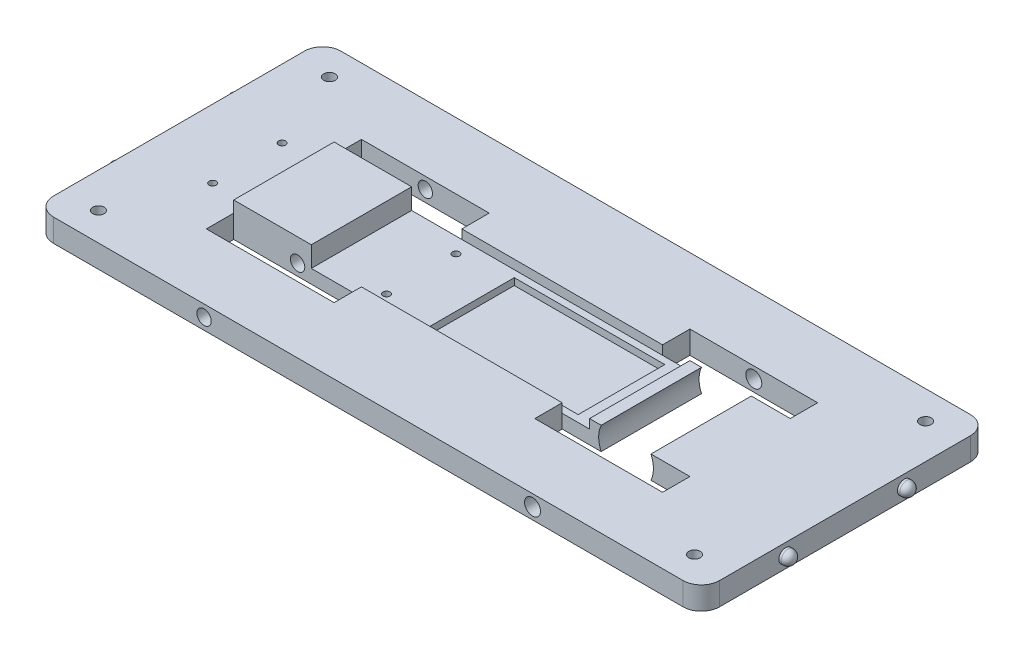
SolidWorks part; units mm, degrees
ref_plane "Front Plane" through (0, 0, 0) normal (0, 0, 1) x (1, 0, 0)
ref_plane "Top Plane" through (0, 0, 0) normal (0, 1, 0) x (1, 0, 0)
ref_plane "Right Plane" through (0, 0, 0) normal (1, 0, 0) x (0, 0, -1)
sketch "Sketch1" plane through (0, 0, 0) normal (0, 1, 0) x (1, 0, 0)
  line L1 (-69, 31.5) -> (69, 31.5)
  line L2 (-69, 31.5) -> (-69, -31.5)
  line L3 (-69, -31.5) -> (69, -31.5)
  line L4 (69, 31.5) -> (69, -31.5)
  line L5 (-69, 31.5) -> (69, -31.5) construction
  line L6 (-69, -31.5) -> (69, 31.5) construction
  point P0 (0, 0)
  dimension "D1" = 138
  dimension "D2" = 63
extrude "Boss-Extrude1" add sketch "Sketch1" along normal mid plane 5
sketch "Sketch3" plane through (0, 2.5, 0) normal (0, 1, 0) x (1, 0, 0)
  line L1 (-50, -11) -> (-22, -11)
  line L2 (-50, -11) -> (-50, -17)
  line L3 (-50, -17) -> (-22, -17)
  line L4 (-22, -11) -> (-22, -17)
  line L6 (0, -2.75) -> (0, 2.75) construction
  line L7 (50, -17) -> (22, -17)
  line L8 (22, -11) -> (22, -17)
  line L9 (50, -11) -> (22, -11)
  line L10 (50, -11) -> (50, -17)
  line L11 (-2.75, 0) -> (2.75, 0) construction
  line L12 (50, 11) -> (50, 17)
  line L13 (50, 11) -> (22, 11)
  line L14 (22, 11) -> (22, 17)
  line L15 (50, 17) -> (22, 17)
  line L16 (-50, 17) -> (-22, 17)
  line L17 (-22, 11) -> (-22, 17)
  line L18 (-50, 11) -> (-22, 11)
  line L19 (-50, 11) -> (-50, 17)
  dimension "D1" = 22
  dimension "D2" = 6
  dimension "D3" = 28
extrude "Cut-Extrude2" cut sketch "Sketch3" against normal blind 10
sketch "Sketch4" plane through (0, 2.5, 0) normal (0, 1, 0) x (1, 0, 0)
  line L0 (-22, -11) -> (-50, -11) construction
  line L1 (-33, -11) -> (28, -11)
  line L2 (-33, -11) -> (-33, 11)
  line L3 (-33, 11) -> (28, 11)
  line L4 (28, -11) -> (28, 11)
  line L5 (22, 11) -> (50, 11) construction
  line L6 (-50, -11) -> (-50, -17) construction
  line L7 (50, -17) -> (50, -11) construction
  dimension "D1" = 17
  dimension "D2" = 22
extrude "Cut-Extrude3" cut sketch "Sketch4" against normal blind 2
sketch "Sketch5" plane through (0, 0, -11) normal (0, 0, -1) x (-1, 0, 0)
  line L2 (50, -2.5) -> (50, 2.5) construction
  line L4 (0, 2.5) -> (0, -2.563)
  line L5 (-69, 2.5) -> (69, 2.5) construction
  line L6 (0, 2.75) -> (0, -2.75) construction
  line L7 (22, 2.5) -> (50, 2.5) construction
  circle A0 centre (36, 0) radius 1.575
  circle A3 centre (-36, 0) radius 1.75
  dimension "D1" = 3.15
  dimension "D4" = 3.5
  dimension "D2" = 2.5
  dimension "D3" = 14
sketch "Sketch6" plane through (0, 0.5, 0) normal (0, 1, 0) x (1, 0, 0)
  line L0 (-2.75, 0) -> (2.75, 0) construction
  line L1 (-9, -9.5) -> (24, -9.5)
  line L2 (-9, -9.5) -> (-9, 9.5)
  line L3 (-9, 9.5) -> (24, 9.5)
  line L4 (24, -9.5) -> (24, 9.5)
  line L5 (28, -11) -> (28, 11) construction
  dimension "D1" = 33
  dimension "D2" = 19
  dimension "D3" = 9.5
  dimension "D4" = 4
extrude "Cut-Extrude5" cut sketch "Sketch6" against normal blind 1.5
sketch "Sketch11" plane through (0, 2.5, 0) normal (0, 1, 0) x (1, 0, 0)
  line L0 (-2.75, 0) -> (2.75, 0) construction
  line L1 (-69, 31.5) -> (-69, -31.5) construction
  circle A0 centre (-58, 7.62) radius 0.775
  circle A1 centre (-19.9, 7.62) radius 0.775
  circle A2 centre (-58, -7.62) radius 0.775
  circle A3 centre (-19.9, -7.62) radius 0.775
  dimension "D1" = 1.55
  dimension "D3" = 7.62
  dimension "D4" = 11
  dimension "D2" = 2
extrude "Cut-Extrude8" cut sketch "Sketch11" against normal blind 6
extrude "Cut-Extrude9" cut sketch "Sketch5" against normal through all both and the other way through all
sketch "Sketch16" plane through (0, 0, 0) normal (0, 0, 1) x (1, 0, 0)
  circle A1 centre (36, 0) radius 6
  dimension "D1" = 12
extrude "Cut-Extrude10" cut sketch "Sketch16" against normal mid plane 22
sketch "Sketch19" plane through (0, 2.5, 0) normal (0, 1, 0) x (1, 0, 0)
  line L1 (69, 31.5) -> (-69, 31.5) construction
  line L2 (-2.75, 0) -> (2.75, 0) construction
  line L3 (0, -2.75) -> (0, 2.75) construction
  circle A0 centre (-65.33, 25.32) radius 1.25
  circle A1 centre (-65.33, -25.32) radius 1.25
  circle A2 centre (65.33, -25.32) radius 1.25
  circle A3 centre (65.33, 25.32) radius 1.25
  point P16 (-46.1047, 23.7958)
  point P17 (65.33, -25.32)
  point P18 (65.33, 25.32)
  point P19 (65.33, -25.32)
  point P20 (65.33, 25.32)
  point P21 (-65.33, -25.32)
  point P22 (-65.33, 25.32)
  dimension "D1" = 2.5
  dimension "D2" = 130.66
  dimension "D3" = 6.18
extrude "Cut-Extrude12" cut sketch "Sketch19" against normal blind 5
sketch "Sketch21" plane through (0, 0, 0) normal (0, 0, 1) x (1, 0, 0)
  line L0 (-33, 0.5) -> (-33, 2.5) construction
  line L6 (-50, 2.5) -> (-33, 2.5) construction
  line L7 (-33, 5) -> (-50, 5)
  line L8 (-33, 5) -> (-33, 2.5)
  line L9 (-33, 2.5) -> (-50, 2.5)
  line L10 (-50, 5) -> (-50, 2.5)
  dimension "D1" = 2.5
  dimension "D2" = 0
  dimension "D3" = 17
  dimension "D4" = 0
extrude "Boss-Extrude2" add sketch "Sketch21" along normal mid plane 22
sketch "Sketch22" plane through (69, 0, 0) normal (1, 0, 0) x (0, 0, -1)
  line L1 (-31.5, 2.5) -> (31.5, 2.5)
  line L2 (-31.5, 2.5) -> (-31.5, -2.5)
  line L3 (-31.5, -2.5) -> (31.5, -2.5)
  line L4 (31.5, 2.5) -> (31.5, -2.5)
extrude "Boss-Extrude3" add sketch "Sketch22" along normal blind 4
sketch "Sketch23" plane through (73, 0, 0) normal (1, 0, 0) x (0, 0, -1)
  line L0 (0, 2.75) -> (0, -2.75) construction
  circle A0 centre (-13, 0) radius 1.5
  circle A1 centre (13, 0) radius 1.5
  dimension "D1" = 3
  dimension "D2" = 3
  dimension "D3" = 13
  dimension "D4" = 13
extrude "Boss-Extrude4" add sketch "Sketch23" along normal blind 2
mirror "Mirror1" about plane through (0, 0, 0) normal (1, 0, 0) of "Boss-Extrude3"
mirror "Mirror7" about plane through (0, 0, 0) normal (1, 0, 0) of "Boss-Extrude4"
fillet "Fillet3" radius 4 4 edges at (73, 0, 31.5) (73, 0, -31.5) (-73, 0, 31.5) (-73, 0, -31.5)
fillet "Fillet2" radius 1.5 4 edges at (75, 0, -14.5) (75, 0, 11.5) (-75, 0, 11.5) (-75, 0, -14.5)
